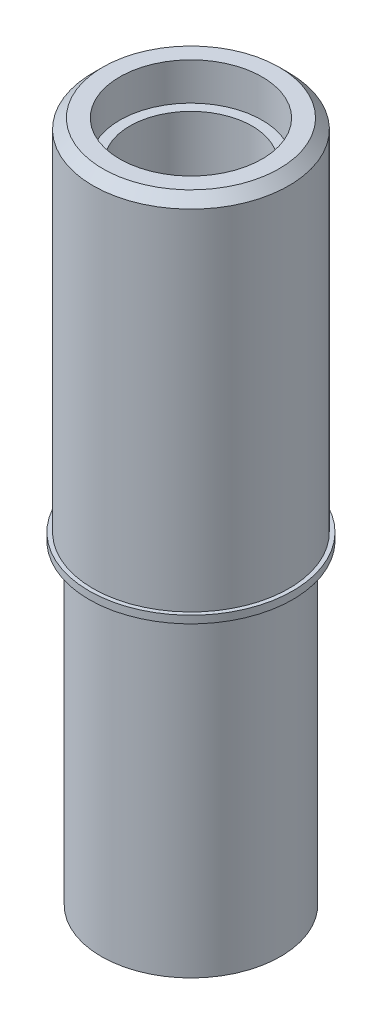
SolidWorks part; units mm, degrees
material "6061-T6 (SS)"
ref_plane "Front Plane" through (0, 0, 0) normal (0, 0, 1) x (1, 0, 0)
ref_plane "Top Plane" through (0, 0, 0) normal (0, 1, 0) x (1, 0, 0)
ref_plane "Right Plane" through (0, 0, 0) normal (1, 0, 0) x (0, 0, -1)
sketch "Sketch1" plane through (0, 0, 0) normal (1, 0, 0) x (0, 0, -1)
  line L0 (0, 53.086) -> (0, -53.086) construction
  line L1 (0, 0) -> (9.525, 0) construction
  line L2 (11.0935, 53.086) -> (15.875, 53.086) construction
  line L3 (9.525, 47.244) -> (9.525, -47.244) construction
  line L4 (11.0935, -53.086) -> (15.875, -53.086) construction
  line L5 (15.875, 53.086) -> (15.875, -53.086) construction
  line L6 (11.0935, -53.086) -> (11.0934, -47.244)
  line L7 (9.525, -47.244) -> (11.0934, -47.244)
  line L8 (9.525, 47.244) -> (11.0934, 47.244)
  line L9 (11.0935, 53.086) -> (11.0934, 47.244)
  line L10 (11.0935, -53.086) -> (13.97, -53.086)
  line L11 (13.97, -53.086) -> (13.97, -3.961)
  line L12 (13.97, -3.961) -> (15.875, -3.961)
  line L13 (15.875, -3.961) -> (15.875, -2.794)
  line L14 (15.875, -2.794) -> (15.2527, -2.794)
  line L15 (15.2527, -2.794) -> (15.2527, 53.086)
  line L16 (15.2527, 53.086) -> (11.0935, 53.086)
  line L17 (9.525, 47.244) -> (9.525, -47.244)
  point P5 (0, 0)
  dimension "D1" = 19.05
  dimension "D2" = 31.75
  dimension "D3" = 106.172
  dimension "D4" = 5.842
  dimension "D5" = 22.1869
  dimension "D6" = 30.5054
  dimension "D7" = 49.125
  dimension "D8" = 27.94
  dimension "D9" = 55.88
revolve "Revolve1" add sketch "Sketch1" angle 360 about L0
chamfer "Chamfer1" distance 1.524 angle 45 1 edges at (0, 53.086, 15.2527)
sketch "Sketch2" plane through (0, 0, 0) normal (1, 0, 0) x (0, 0, -1)
  line L0 (15.875, -2.794) -> (-15.875, -2.794) construction
  line L1 (15.875, -3.961) -> (15.24, -3.961)
  line L2 (15.875, -3.961) -> (15.875, -6.604)
  line L3 (15.875, -6.604) -> (15.24, -6.604)
  line L4 (15.24, -3.961) -> (15.24, -6.604)
  line L5 (13.97, -53.086) -> (13.97, -3.961) construction
  line L6 (0, 80.4391) -> (0, -82.1433) construction
  dimension "D1" = 3.81
  dimension "D2" = 1.27
revolve "Middle Octo Lightening" [suppressed] cut sketch "Sketch2" angle 360 about L6
